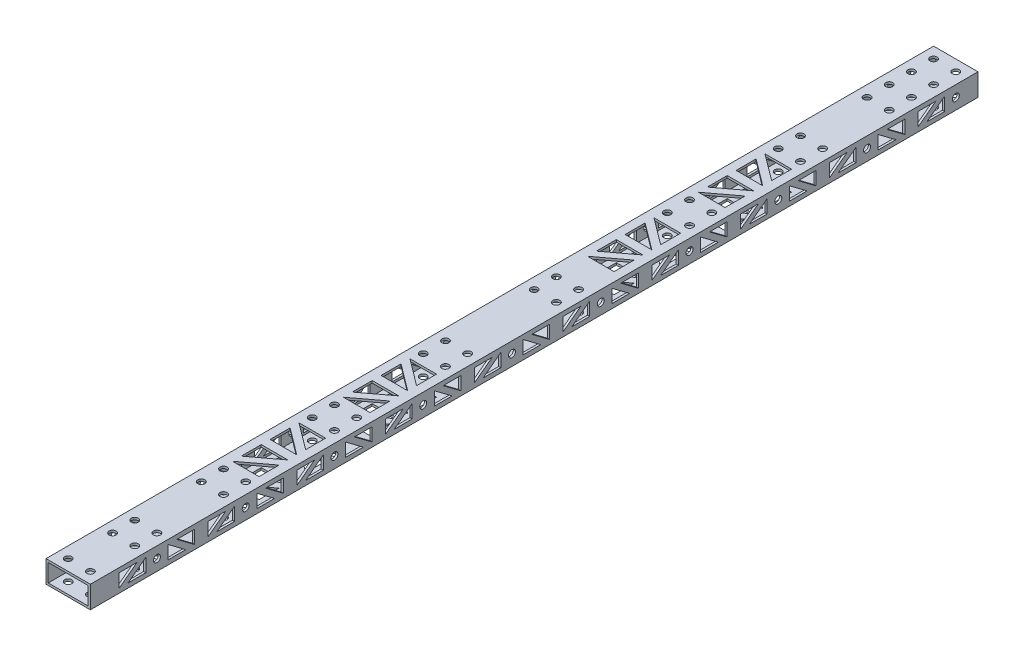
SolidWorks part; units mm, degrees
ref_plane "前视基准面" through (0, 0, 0) normal (0, 0, 1) x (1, 0, 0)
ref_plane "上视基准面" through (0, 0, 0) normal (0, 1, 0) x (1, 0, 0)
ref_plane "右视基准面" through (0, 0, 0) normal (1, 0, 0) x (0, 0, -1)
other "Configuration Table"
sketch "草图1" plane through (0, 0, 0) normal (0, 0, 1) x (1, 0, 0)
  line L1 (0, 0) -> (20, 0)
  line L2 (0, 0) -> (0, -10)
  line L3 (0, -10) -> (20, -10)
  line L4 (20, 0) -> (20, -10)
  dimension "D1" = 20
  dimension "D2" = 10
extrude "拉伸-薄壁1" add sketch "草图1" along normal blind 400 thin
sketch "草图2" plane through (0, 0, 0) normal (0, 1, 0) x (1, 0, 0)
  line L0 (0, -10) -> (20, -10) construction
  line L1 (0, -400) -> (0, 0) construction
  line L2 (20, -400) -> (20, 0) construction
  line L3 (20, 0) -> (0, 0) construction
  line L4 (10, 0) -> (10, -10) construction
  line L5 (0, -20) -> (20, -20) construction
  circle A0 centre (15, -5) radius 1.575
  circle A1 centre (5, -5) radius 1.575
  circle A2 centre (5, -15) radius 1.575
  circle A3 centre (15, -15) radius 1.575
  circle A4 centre (15, -25) radius 1.575
  circle A5 centre (5, -25) radius 1.575
  circle A6 centre (5, -35) radius 1.575
  circle A7 centre (15, -35) radius 1.575
  dimension "D2" = 3.15
  dimension "D1" = 10
  dimension "D3" = 5
  dimension "D4" = 5
  dimension "D5" = 20
extrude "切除-拉伸1" cut sketch "草图2" against normal through all
sketch "草图3" plane through (0, 0, 0) normal (0, 1, 0) x (1, 0, 0)
  line L0 (10, -400) -> (10, 0) construction
  line L1 (20, -400) -> (0, -400) construction
  line L2 (20, 0) -> (0, 0) construction
  line L3 (0, -370) -> (20, -370) construction
  line L4 (0, -400) -> (0, 0) construction
  line L5 (20, -400) -> (20, 0) construction
  line L6 (0, -350) -> (20, -350) construction
  line L7 (0, -200) -> (20, -200) construction
  line L8 (4, -320) -> (16, -320)
  line L9 (16, -320) -> (16, -311)
  line L10 (16, -311) -> (4, -320)
  line L11 (4, -307) -> (4, -316)
  line L12 (4, -316) -> (16, -307)
  line L13 (16, -307) -> (4, -307)
  line L14 (0, -305) -> (20, -305) construction
  line L15 (16, -303) -> (4, -303)
  line L16 (4, -294) -> (16, -303)
  line L17 (4, -303) -> (4, -294)
  line L18 (16, -299) -> (4, -290)
  line L19 (16, -290) -> (16, -299)
  line L20 (4, -290) -> (16, -290)
  line L21 (4, -240) -> (16, -240)
  line L22 (16, -240) -> (16, -249)
  line L23 (16, -249) -> (4, -240)
  line L24 (4, -253) -> (4, -244)
  line L25 (4, -244) -> (16, -253)
  line L26 (16, -253) -> (4, -253)
  line L27 (16, -257) -> (4, -257)
  line L28 (4, -257) -> (4, -266)
  line L29 (4, -266) -> (16, -257)
  line L30 (16, -261) -> (4, -270)
  line L31 (16, -270) -> (16, -261)
  line L32 (4, -270) -> (16, -270)
  line L33 (0, -95) -> (20, -95) construction
  line L34 (4, -110) -> (16, -110)
  line L35 (16, -110) -> (16, -101)
  line L36 (16, -101) -> (4, -110)
  line L37 (4, -97) -> (4, -106)
  line L38 (4, -106) -> (16, -97)
  line L39 (16, -97) -> (4, -97)
  line L40 (16, -93) -> (4, -93)
  line L41 (4, -84) -> (16, -93)
  line L42 (4, -93) -> (4, -84)
  line L43 (16, -89) -> (4, -80)
  line L44 (16, -80) -> (16, -89)
  line L45 (4, -80) -> (16, -80)
  line L46 (4, -130) -> (16, -130)
  line L47 (16, -130) -> (16, -139)
  line L48 (16, -139) -> (4, -130)
  line L49 (4, -134) -> (16, -143)
  line L50 (4, -143) -> (4, -134)
  line L51 (16, -143) -> (4, -143)
  line L52 (16, -147) -> (4, -147)
  line L53 (4, -156) -> (16, -147)
  line L54 (4, -147) -> (4, -156)
  line L55 (16, -151) -> (4, -160)
  line L56 (16, -160) -> (16, -151)
  line L57 (4, -160) -> (16, -160)
  circle A0 centre (5, -395) radius 1.575
  circle A1 centre (15, -395) radius 1.575
  circle A2 centre (5, -375) radius 1.575
  circle A3 centre (15, -375) radius 1.575
  circle A4 centre (5, -365) radius 1.575
  circle A5 centre (15, -365) radius 1.575
  circle A52 centre (5, -355) radius 1.575 [skipped]
  circle A53 centre (15, -355) radius 1.575 [skipped]
  circle A54 centre (5, -345) radius 1.575 [skipped]
  circle A55 centre (15, -345) radius 1.575 [skipped]
  circle A56 centre (5, -335) radius 1.575 [skipped]
  circle A57 centre (15, -335) radius 1.575 [skipped]
  circle A58 centre (5, -325) radius 1.575 [skipped]
  circle A59 centre (15, -325) radius 1.575 [skipped]
  circle A60 centre (5, -315) radius 1.575 [skipped]
  circle A61 centre (15, -315) radius 1.575 [skipped]
  circle A62 centre (5, -305) radius 1.575 [skipped]
  circle A63 centre (15, -305) radius 1.575 [skipped]
  circle A64 centre (5, -295) radius 1.575 [skipped]
  circle A65 centre (15, -295) radius 1.575 [skipped]
  circle A66 centre (5, -285) radius 1.575 [skipped]
  circle A67 centre (15, -285) radius 1.575 [skipped]
  circle A68 centre (5, -275) radius 1.575 [skipped]
  circle A69 centre (15, -275) radius 1.575 [skipped]
  circle A70 centre (5, -265) radius 1.575 [skipped]
  circle A71 centre (15, -265) radius 1.575 [skipped]
  circle A72 centre (5, -255) radius 1.575 [skipped]
  circle A73 centre (15, -255) radius 1.575 [skipped]
  circle A74 centre (5, -245) radius 1.575 [skipped]
  circle A75 centre (15, -245) radius 1.575 [skipped]
  circle A76 centre (5, -235) radius 1.575 [skipped]
  circle A77 centre (15, -235) radius 1.575 [skipped]
  circle A78 centre (5, -225) radius 1.575 [skipped]
  circle A79 centre (15, -225) radius 1.575 [skipped]
  circle A80 centre (5, -215) radius 1.575 [skipped]
  circle A81 centre (15, -215) radius 1.575 [skipped]
  circle A82 centre (5, -205) radius 1.575 [skipped]
  circle A83 centre (15, -205) radius 1.575 [skipped]
  circle A84 centre (5, -195) radius 1.575 [skipped]
  circle A85 centre (15, -195) radius 1.575 [skipped]
  circle A86 centre (5, -185) radius 1.575 [skipped]
  circle A87 centre (15, -185) radius 1.575 [skipped]
  circle A88 centre (5, -175) radius 1.575 [skipped]
  circle A89 centre (15, -175) radius 1.575 [skipped]
  circle A90 centre (5, -165) radius 1.575 [skipped]
  circle A91 centre (15, -165) radius 1.575 [skipped]
  circle A92 centre (5, -155) radius 1.575 [skipped]
  circle A93 centre (15, -155) radius 1.575 [skipped]
  circle A94 centre (5, -145) radius 1.575 [skipped]
  circle A95 centre (15, -145) radius 1.575 [skipped]
  circle A96 centre (5, -135) radius 1.575 [skipped]
  circle A97 centre (15, -135) radius 1.575 [skipped]
  circle A114 centre (15, -335) radius 1.575
  circle A115 centre (5, -335) radius 1.575
  circle A116 centre (15, -325) radius 1.575
  circle A117 centre (5, -325) radius 1.575
  circle A118 centre (5, -275) radius 1.575
  circle A119 centre (15, -275) radius 1.575
  circle A120 centre (5, -285) radius 1.575
  circle A121 centre (15, -285) radius 1.575
  circle A122 centre (5, -225) radius 1.575
  circle A123 centre (15, -225) radius 1.575
  circle A124 centre (5, -235) radius 1.575
  circle A125 centre (15, -235) radius 1.575
  circle A126 centre (5, -175) radius 1.575
  circle A127 centre (15, -175) radius 1.575
  circle A128 centre (5, -185) radius 1.575
  circle A129 centre (15, -185) radius 1.575
  circle A130 centre (15, -115) radius 1.575
  circle A131 centre (5, -115) radius 1.575
  circle A132 centre (15, -125) radius 1.575
  circle A133 centre (5, -125) radius 1.575
  circle A134 centre (5, -75) radius 1.575
  circle A135 centre (15, -75) radius 1.575
  circle A136 centre (5, -65) radius 1.575
  circle A137 centre (15, -65) radius 1.575
  dimension "D1" = 3.15
  dimension "D4" = 3.15
  dimension "D2" = 5
  dimension "D3" = 5
  dimension "D5" = 5
  dimension "D6" = 5
  dimension "D7" = 30
  dimension "D9" = 10
  dimension "D11" = 50
  dimension "D12" = 9
  dimension "D10" = 20
  dimension "D13" = 12
  dimension "D14" = 9
  dimension "D15" = 12
  dimension "D16" = 4
  dimension "D17" = 13
  dimension "D18" = 5
  dimension "D19" = 20
  dimension "D21" = 50
  dimension "D8" = 25
  dimension "D20" = 2
extrude "切除-拉伸2" cut sketch "草图3" against normal blind 10
sketch "草图4" plane through (0, 0, 0) normal (-1, 0, 0) x (0, 0, 1)
  line L0 (0, 0) -> (0, -10) construction
  line L1 (400, -10) -> (0, -10) construction
  line L2 (15, -2) -> (15, -8)
  line L3 (15, -8) -> (23, -8)
  line L4 (23, -8) -> (15, -2)
  line L5 (19, -2) -> (27, -8)
  line L6 (27, -8) -> (27, -2)
  line L7 (27, -2) -> (19, -2)
  line L8 (400, 0) -> (0, 0) construction
  line L9 (63, -8) -> (55, -2)
  line L10 (55, -2) -> (55, -8)
  line L11 (55, -8) -> (63, -8)
  line L12 (67, -2) -> (59, -2)
  line L13 (59, -2) -> (67, -8)
  line L14 (67, -8) -> (67, -2)
  line L15 (103, -8) -> (95, -2)
  line L16 (95, -2) -> (95, -8)
  line L17 (95, -8) -> (103, -8)
  line L18 (107, -2) -> (99, -2)
  line L19 (99, -2) -> (107, -8)
  line L20 (107, -8) -> (107, -2)
  line L21 (143, -8) -> (135, -2)
  line L22 (135, -2) -> (135, -8)
  line L23 (135, -8) -> (143, -8)
  line L24 (147, -2) -> (139, -2)
  line L25 (139, -2) -> (147, -8)
  line L26 (147, -8) -> (147, -2)
  line L27 (183, -8) -> (175, -2)
  line L28 (175, -2) -> (175, -8)
  line L29 (175, -8) -> (183, -8)
  line L30 (187, -2) -> (179, -2)
  line L31 (179, -2) -> (187, -8)
  line L32 (187, -8) -> (187, -2)
  line L33 (223, -8) -> (215, -2)
  line L34 (215, -2) -> (215, -8)
  line L35 (215, -8) -> (223, -8)
  line L36 (227, -2) -> (219, -2)
  line L37 (219, -2) -> (227, -8)
  line L38 (227, -8) -> (227, -2)
  line L39 (263, -8) -> (255, -2)
  line L40 (255, -2) -> (255, -8)
  line L41 (255, -8) -> (263, -8)
  line L42 (267, -2) -> (259, -2)
  line L43 (259, -2) -> (267, -8)
  line L44 (267, -8) -> (267, -2)
  line L45 (303, -8) -> (295, -2)
  line L46 (295, -2) -> (295, -8)
  line L47 (295, -8) -> (303, -8)
  line L48 (307, -2) -> (299, -2)
  line L49 (299, -2) -> (307, -8)
  line L50 (307, -8) -> (307, -2)
  line L51 (343, -8) -> (335, -2)
  line L52 (335, -2) -> (335, -8)
  line L53 (335, -8) -> (343, -8)
  line L54 (347, -2) -> (339, -2)
  line L55 (339, -2) -> (347, -8)
  line L56 (347, -8) -> (347, -2)
  line L57 (383, -8) -> (375, -2)
  line L58 (375, -2) -> (375, -8)
  line L59 (375, -8) -> (383, -8)
  line L60 (387, -2) -> (379, -2)
  line L61 (379, -2) -> (387, -8)
  line L62 (387, -8) -> (387, -2)
  line L123 (30, 0) -> (30, -10) construction
  line L124 (33, -2) -> (41, -2)
  line L125 (33, -8) -> (33, -2)
  line L126 (41, -2) -> (33, -8)
  line L127 (37, -8) -> (45, -2)
  line L128 (45, -8) -> (37, -8)
  line L129 (45, -2) -> (45, -8)
  line L130 (73, -2) -> (81, -2)
  line L131 (73, -8) -> (73, -2)
  line L132 (81, -2) -> (73, -8)
  line L133 (77, -8) -> (85, -2)
  line L134 (85, -2) -> (85, -8)
  line L135 (85, -8) -> (77, -8)
  line L136 (113, -2) -> (121, -2)
  line L137 (113, -8) -> (113, -2)
  line L138 (121, -2) -> (113, -8)
  line L139 (117, -8) -> (125, -2)
  line L140 (125, -2) -> (125, -8)
  line L141 (125, -8) -> (117, -8)
  line L142 (153, -2) -> (161, -2)
  line L143 (153, -8) -> (153, -2)
  line L144 (161, -2) -> (153, -8)
  line L145 (157, -8) -> (165, -2)
  line L146 (165, -2) -> (165, -8)
  line L147 (165, -8) -> (157, -8)
  line L148 (193, -2) -> (201, -2)
  line L149 (193, -8) -> (193, -2)
  line L150 (201, -2) -> (193, -8)
  line L151 (197, -8) -> (205, -2)
  line L152 (205, -2) -> (205, -8)
  line L153 (205, -8) -> (197, -8)
  line L154 (233, -2) -> (241, -2)
  line L155 (233, -8) -> (233, -2)
  line L156 (241, -2) -> (233, -8)
  line L157 (237, -8) -> (245, -2)
  line L158 (245, -2) -> (245, -8)
  line L159 (245, -8) -> (237, -8)
  line L160 (273, -2) -> (281, -2)
  line L161 (273, -8) -> (273, -2)
  line L162 (281, -2) -> (273, -8)
  line L163 (277, -8) -> (285, -2)
  line L164 (285, -2) -> (285, -8)
  line L165 (285, -8) -> (277, -8)
  line L166 (313, -2) -> (321, -2)
  line L167 (313, -8) -> (313, -2)
  line L168 (321, -2) -> (313, -8)
  line L169 (317, -8) -> (325, -2)
  line L170 (325, -2) -> (325, -8)
  line L171 (325, -8) -> (317, -8)
  line L172 (353, -2) -> (361, -2)
  line L173 (353, -8) -> (353, -2)
  line L174 (361, -2) -> (353, -8)
  line L175 (357, -8) -> (365, -2)
  line L176 (365, -2) -> (365, -8)
  line L177 (365, -8) -> (357, -8)
  circle A0 centre (10, -5) radius 1.575
  circle A1 centre (50, -5) radius 1.575
  circle A2 centre (90, -5) radius 1.575
  circle A3 centre (130, -5) radius 1.575
  circle A4 centre (170, -5) radius 1.575
  circle A5 centre (210, -5) radius 1.575
  circle A6 centre (250, -5) radius 1.575
  circle A7 centre (290, -5) radius 1.575
  circle A8 centre (330, -5) radius 1.575
  circle A9 centre (370, -5) radius 1.575
  point P155 (0, 0)
  dimension "D1" = 3.15
  dimension "D2" = 10
  dimension "D3" = 5
  dimension "D5" = 40
  dimension "D7" = 40
  dimension "D8" = 6
  dimension "D9" = 8
  dimension "D10" = 8
  dimension "D11" = 6
  dimension "D12" = 2
  dimension "D13" = 2
  dimension "D14" = 5
  dimension "D15" = 12
  dimension "D17" = 40
  dimension "D18" = 20
  dimension "D20" = 40
  dimension "D4" = 8
  dimension "D6" = 3
  dimension "D16" = 10
  dimension "D19" = 9
extrude "切除-拉伸3" cut sketch "草图4" against normal through all
